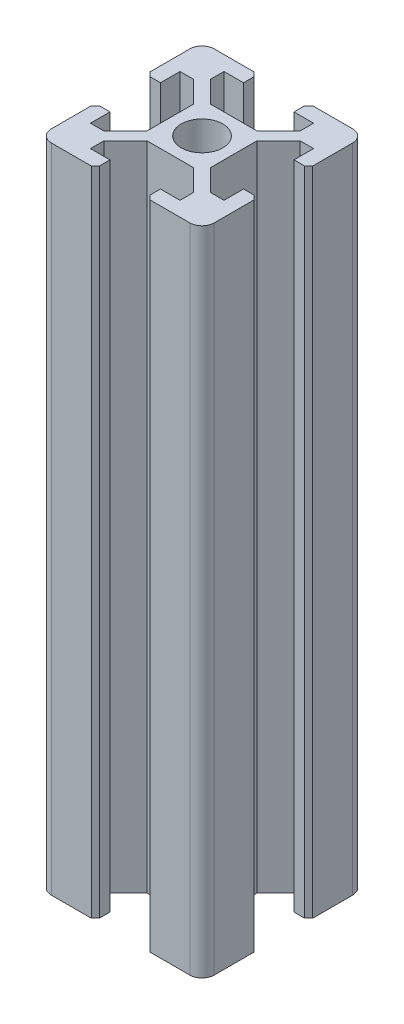
SolidWorks part; units mm, degrees
material "1060 合金"
ref_plane "前视" through (0, 0, 0) normal (0, 0, 1) x (1, 0, 0)
ref_plane "上视" through (0, 0, 0) normal (0, 1, 0) x (1, 0, 0)
ref_plane "右视" through (0, 0, 0) normal (1, 0, 0) x (0, 0, -1)
sketch "草图1" plane through (0, 0, 0) normal (0, 1, 0) x (1, 0, 0)
  line L0 (13.9, 12.8393) -> (13.9, 7.1607)
  line L5 (12.8393, 6.1) -> (7.1607, 6.1)
  line L6 (0, 20) -> (20, 0) construction
  line L7 (20, 20) -> (0, 0) construction
  line L8 (4.5, 18.2) -> (6.9, 18.2)
  line L9 (18.2, 4.5) -> (18.2, 6.9)
  line L10 (4.5, 1.8) -> (6.9, 1.8)
  line L11 (1.8, 4.5) -> (1.8, 6.9)
  line L12 (3.4393, 15.5) -> (6.1, 12.8393)
  line L16 (1.5, 0) -> (6.4, 0)
  line L17 (4.5, 16.5607) -> (7.1607, 13.9)
  line L18 (15.5, 16.5607) -> (12.8393, 13.9)
  line L19 (16.5607, 15.5) -> (13.9, 12.8393)
  line L21 (0, 13.6) -> (0.5, 13.1)
  line L22 (19.4697, 20.5303) -> (-0.5303, 0.5303) construction
  line L23 (20.5303, 19.4697) -> (0.5303, -0.5303) construction
  line L24 (13.9, 7.1607) -> (16.5607, 4.5)
  line L25 (12.8393, 6.1) -> (15.5, 3.4393)
  line L28 (7.1607, 6.1) -> (4.5, 3.4393)
  line L30 (6.1, 7.1607) -> (3.4393, 4.5)
  line L31 (0.5, 6.9) -> (1.8, 6.9)
  line L32 (0.5, 13.1) -> (1.8, 13.1)
  line L33 (6.9, 19.5) -> (6.9, 18.2)
  line L34 (13.1, 19.5) -> (13.1, 18.2)
  line L35 (6.9, 1.8) -> (6.9, 0.5)
  line L36 (6.1, 7.1607) -> (6.1, 12.8393)
  line L37 (13.1, 1.8) -> (13.1, 0.5)
  line L38 (7.1607, 13.9) -> (12.8393, 13.9)
  line L39 (1.8, 13.1) -> (1.8, 15.5)
  line L40 (0, 1.5) -> (0, 6.4)
  line L41 (18.2, 13.1) -> (19.5, 13.1)
  line L42 (1.8, 4.5) -> (3.4393, 4.5)
  line L44 (18.2, 6.9) -> (19.5, 6.9)
  line L46 (13.1, 1.8) -> (15.5, 1.8)
  line L51 (13.1, 18.2) -> (15.5, 18.2)
  line L54 (18.2, 13.1) -> (18.2, 15.5)
  line L56 (4.5, 1.8) -> (4.5, 3.4393)
  line L57 (1.5, 20) -> (6.4, 20)
  line L58 (0, 18.5) -> (0, 13.6)
  line L59 (1.8, 15.5) -> (3.4393, 15.5)
  line L60 (4.5, 18.2) -> (4.5, 16.5607)
  line L61 (18.5, 20) -> (13.6, 20)
  line L62 (20, 18.5) -> (20, 13.6)
  line L63 (18.2, 15.5) -> (16.5607, 15.5)
  line L64 (15.5, 18.2) -> (15.5, 16.5607)
  line L65 (18.5, 0) -> (13.6, 0)
  line L66 (20, 1.5) -> (20, 6.4)
  line L67 (18.2, 4.5) -> (16.5607, 4.5)
  line L68 (15.5, 1.8) -> (15.5, 3.4393)
  line L69 (0, 6.4) -> (0.5, 6.9)
  line L70 (6.4, 0) -> (6.9, 0.5)
  line L72 (13.6, 0) -> (13.1, 0.5)
  line L73 (20, 6.4) -> (19.5, 6.9)
  line L75 (20, 13.6) -> (19.5, 13.1)
  line L76 (13.6, 20) -> (13.1, 19.5)
  line L77 (6.4, 20) -> (6.9, 19.5)
  circle A0 centre (10, 10) radius 2.55
  arc A1 (18.5, 20) -> (20, 18.5) centre (18.5, 18.5) cw
  arc A2 (0, 18.5) -> (1.5, 20) centre (1.5, 18.5) cw
  arc A3 (0, 1.5) -> (1.5, 0) centre (1.5, 1.5) ccw
  arc A4 (20, 1.5) -> (18.5, 0) centre (18.5, 1.5) cw
  dimension "D3" = 5.1
  dimension "D5" = 1.5
  dimension "D6" = 1.5
  dimension "D7" = 1.5
  dimension "D8" = 1.5
  dimension "D1" = 20
  dimension "D2" = 20
extrude "凸台-拉伸2" add sketch "草图1" along normal blind 80 contours L51 L64 L18 L38 L17 L60 L8 L33 L77 L57 A2 L58 L21 L32 L39 L59 L12 L36 L30 L42 L11 L31 L69 L40 A3 L16 L70 L35 L10 L56 L28 L5 L25 L68 L46 L37 L72 L65 A4 L66 L73 L44 L9 L67 L24 L0 L19 L63 L54 L41 L75 L62 A1 L61 L76 L34
sketch "草图4" plane through (0, 0, 0) normal (0, -1, 0) x (1, 0, 0)
  circle A4 centre (10, -10) radius 2.55
  dimension "D1" = 5.1
extrude "切除-拉伸2" cut sketch "草图4" against normal through all
